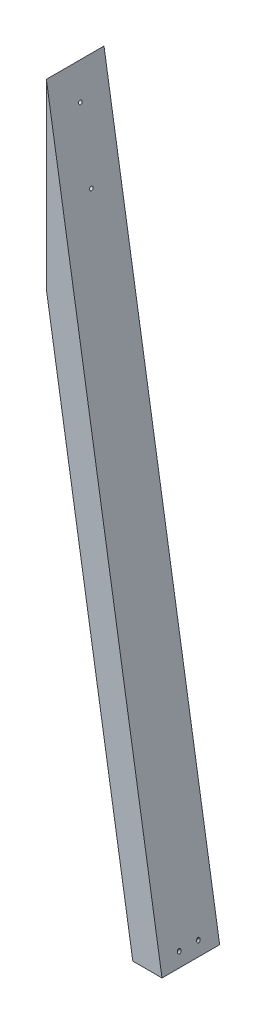
SolidWorks part; units mm, degrees
ref_plane "Front Plane" through (0, 0, 0) normal (0, 0, 1) x (1, 0, 0)
ref_plane "Top Plane" through (0, 0, 0) normal (0, 1, 0) x (1, 0, 0)
ref_plane "Right Plane" through (0, 0, 0) normal (1, 0, 0) x (0, 0, -1)
sketch "Sketch1" plane through (0, 0, 0) normal (0, 0, 1) x (1, 0, 0)
  line L0 (0, 0) -> (0, 1524) construction
  line L1 (-457.2, 0) -> (457.2, 0) construction
  line L2 (0, 949.4617) -> (0, 1270)
  line L3 (0, 1270) -> (203.8502, 0)
  line L4 (203.8502, 0) -> (152.4, 0)
  line L5 (152.4, 0) -> (0, 949.4617)
  point P5 (0, 0)
  dimension "D1" = 914.4
  dimension "D2" = 1524
  dimension "D3" = 50.8
  dimension "D4" = 1270
  dimension "D5" = 152.4
extrude "Boss-Extrude1" add sketch "Sketch1" along normal blind 101.6
sketch "Sketch2" plane through (0, 0, 0) normal (-1, 0, 0) x (0, 0, 1)
  line L0 (0, 1213.8247) -> (50.8, 1213.8247) construction
  line L1 (50.8, 1213.8247) -> (101.6, 1213.8247) construction
  line L2 (101.6, 1270) -> (101.6, 949.4617) construction
  circle A0 centre (50.8, 1213.8247) radius 3.175
  circle A1 centre (50.8, 1092.1985) radius 3.175
  dimension "D1" = 6.35
  dimension "D2" = 6.35
extrude "Cut-Extrude1" cut sketch "Sketch2" against normal blind 930.148
ref_plane "Plane1" through (101.9251, 101.9251, 0) normal (-0.7071, -0.7071, 0) x (0, 0, -1)
sketch "Sketch3" plane through (101.9251, 101.9251, 0) normal (-0.7071, -0.7071, 0) x (0, 0, -1)
  line L0 (-101.6, 125.9535) -> (-67.7333, 125.9535) construction
  line L1 (-101.6, 107.7631) -> (-101.6, 144.1439) construction
  line L2 (-67.7333, 125.9535) -> (-33.8667, 125.9535) construction
  line L3 (-33.8667, 125.9535) -> (0, 125.9535) construction
  line L4 (0, 107.7631) -> (0, 144.1439) construction
  circle A0 centre (-67.7333, 125.9535) radius 3.175
  circle A1 centre (-33.8667, 125.9535) radius 3.175
  dimension "D1" = 6.35
extrude "Cut-Extrude2" cut sketch "Sketch3" against normal blind 167.132 and the other way blind 129.032
